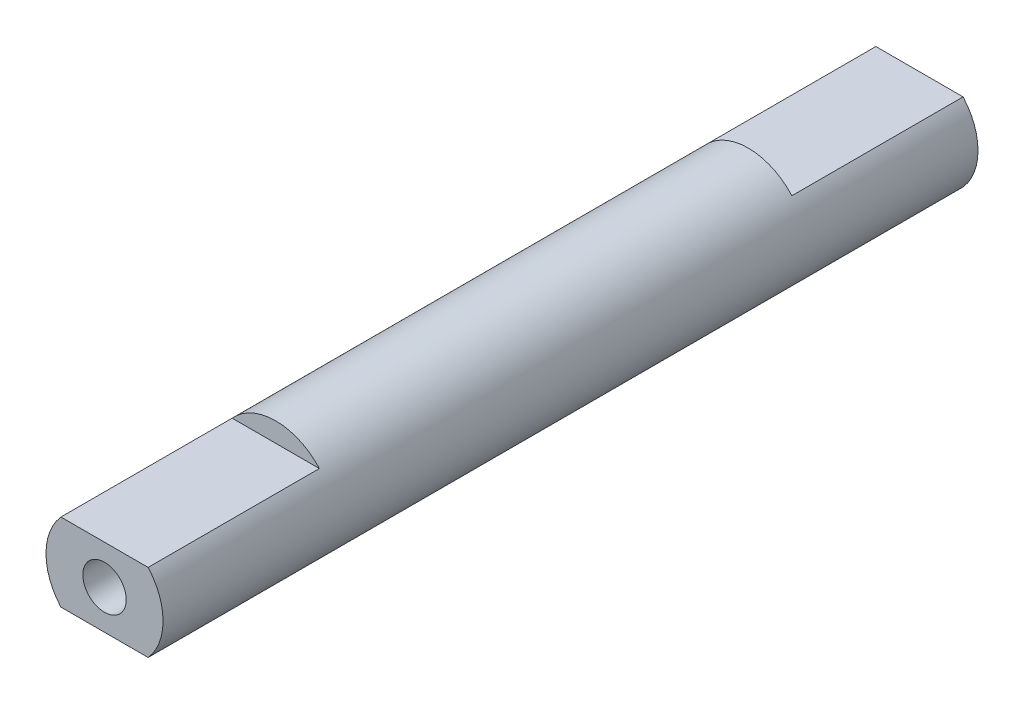
SolidWorks part; units mm, degrees
material "PBT General Purpose"
ref_plane "Alzado" through (0, 0, 0) normal (0, 0, 1) x (1, 0, 0)
ref_plane "Planta" through (0, 0, 0) normal (0, 1, 0) x (1, 0, 0)
ref_plane "Vista lateral" through (0, 0, 0) normal (1, 0, 0) x (0, 0, -1)
sketch "Croquis1" plane through (0, 0, 0) normal (0, 0, 1) x (1, 0, 0)
  circle A0 centre (0, 0) radius 2.7
  circle A1 centre (0, 0) radius 1
  dimension "D1" = 2.7
  dimension "D2" = 2
extrude "Saliente-Extruir1" add sketch "Croquis1" along normal mid plane 37.6 contours A0 A1
sketch "Croquis4" plane through (0, 0, -18.8) normal (0, 0, -1) x (-1, 0, 0)
  line L0 (-2.7, 0) -> (2.7, 0) construction
  line L1 (-2.0125, 1.8) -> (2.0125, 1.8)
  line L2 (-2.0125, -1.8) -> (2.0125, -1.8)
  circle A0 centre (0, 0) radius 2.7 construction
  arc A1 (-2.0125, -1.8) -> (2.0125, -1.8) centre (0, 0) ccw
  arc A2 (2.0125, 1.8) -> (-2.0125, 1.8) centre (0, 0) ccw
  dimension "D1" = 3.6
extrude "Cortar-Extruir2" cut sketch "Croquis4" against normal blind 7.9
mirror "Simetría1" about plane through (0, 0, 0) normal (0, 0, 1) of "Cortar-Extruir2"
